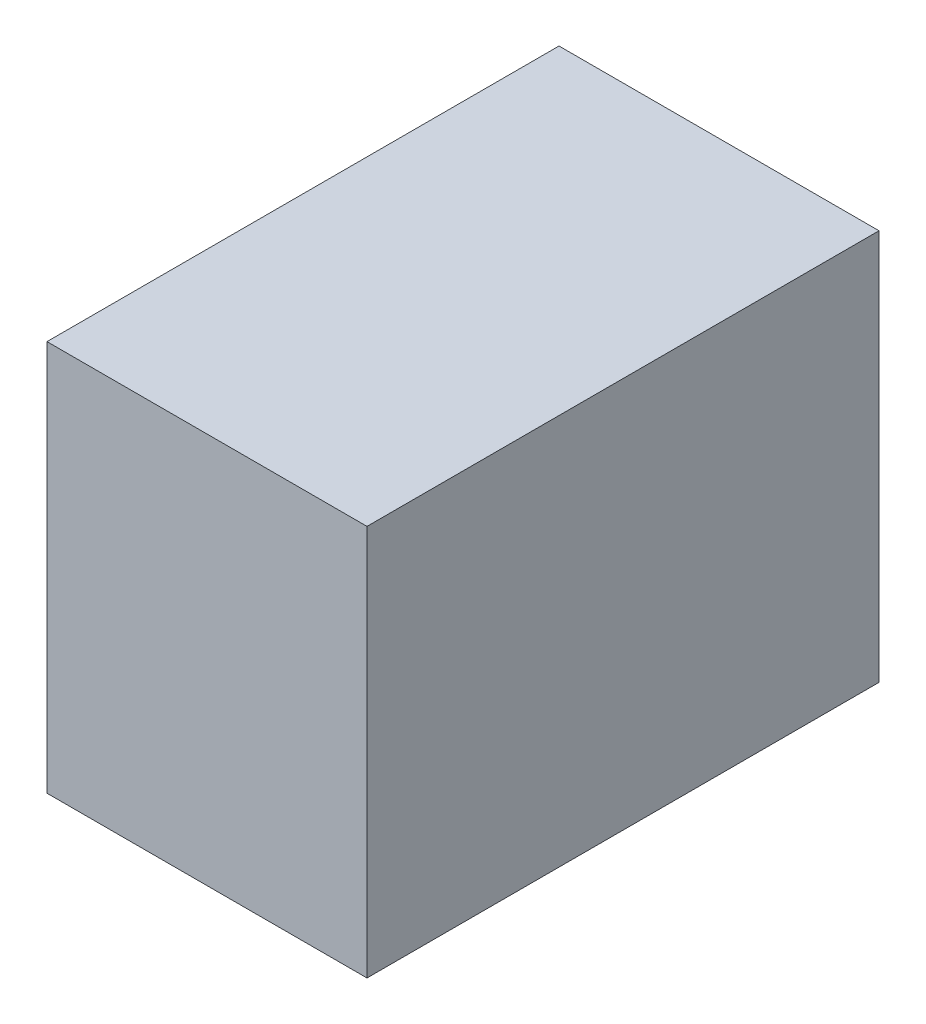
SolidWorks part; units mm, degrees
ref_plane "前视基准面" through (0, 0, 0) normal (0, 0, 1) x (1, 0, 0)
ref_plane "上视基准面" through (0, 0, 0) normal (0, 1, 0) x (1, 0, 0)
ref_plane "右视基准面" through (0, 0, 0) normal (1, 0, 0) x (0, 0, -1)
other "Configuration Table"
sketch "草图1" plane through (0, 0, 0) normal (0, 0, 1) x (1, 0, 0)
  line L1 (31.716, 26.6) -> (40.716, 26.6)
  line L2 (31.716, 26.6) -> (31.716, 37.6)
  line L3 (31.716, 37.6) -> (40.716, 37.6)
  line L4 (40.716, 26.6) -> (40.716, 37.6)
  circle A0 centre (36.216, 33.1) radius 3.25
extrude "PJ002BH_9x11_front_9p5mm_insertion" add sketch "草图1" along normal blind 9.5 from offset 0
sketch "草图2" plane through (0, 0, 0) normal (0, 0, 1) x (1, 0, 0)
  line L1 (31.716, 26.6) -> (40.716, 26.6)
  line L2 (31.716, 26.6) -> (31.716, 37.6)
  line L3 (31.716, 37.6) -> (40.716, 37.6)
  line L4 (40.716, 26.6) -> (40.716, 37.6)
extrude "Jack_rear_body_14p4mm_total" add sketch "草图2" along normal blind 4.9 from offset 9.5
sketch "草图3" plane through (0, 0, 0) normal (0, 0, 1) x (1, 0, 0)
  circle A0 centre (36.216, 33.1) radius 1.25
extrude "2p5mm_centre_pin" add sketch "草图3" along normal blind 9.5 from offset 0
